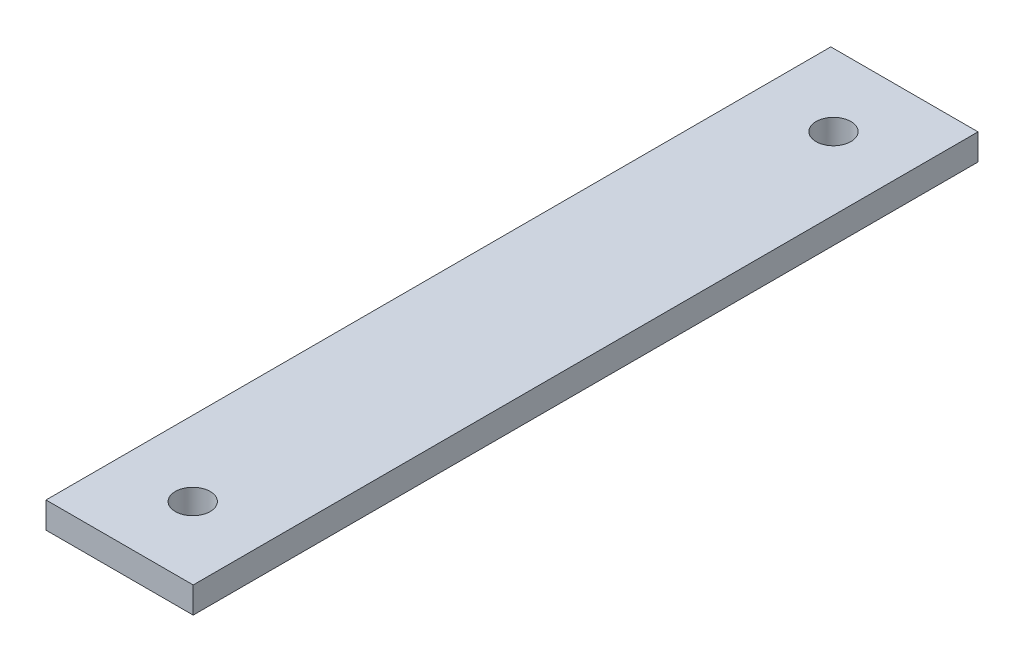
SolidWorks part; units mm, degrees
ref_plane "Piano frontale" through (0, 0, 0) normal (0, 0, 1) x (1, 0, 0)
ref_plane "Piano superiore" through (0, 0, 0) normal (0, 1, 0) x (1, 0, 0)
ref_plane "Piano destro" through (0, 0, 0) normal (1, 0, 0) x (0, 0, -1)
sketch "Schizzo1" plane through (0, 0, 0) normal (0, 1, 0) x (1, 0, 0)
  line L0 (0, 26.1688) -> (0, -29.0254) construction
  line L1 (-37.2892, 0) -> (39.0236, 0) construction
  line L3 (-4.22, -22.5) -> (4.22, -22.5)
  line L4 (-4.22, -22.5) -> (-4.22, 22.5)
  line L5 (-4.22, 22.5) -> (4.22, 22.5)
  line L6 (4.22, -22.5) -> (4.22, 22.5)
  line L7 (-4.22, -22.5) -> (4.22, 22.5) construction
  line L8 (-4.22, 22.5) -> (4.22, -22.5) construction
  point P5 (0, 0)
  dimension "D1" = 45
  dimension "D2" = 8.44
extrude "Estrusione-Estrusione1" add sketch "Schizzo1" along normal blind 1.5
sketch "Schizzo2" plane through (0, 1.5, 0) normal (0, 1, 0) x (1, 0, 0)
  line L0 (0, 23.9805) -> (0, -25.0782) construction
  line L1 (-17.6476, 0) -> (17.7743, 0) construction
  line L2 (-17.6476, 18.37) -> (17.7743, 18.37) construction
  line L3 (4.22, 22.5) -> (-4.22, 22.5) construction
  circle A0 centre (0.0633, 18.37) radius 1
  circle A1 centre (0.0633, -18.37) radius 1
  dimension "D1" = 4.13
extrude "Taglio-Estrusione1" cut sketch "Schizzo2" against normal up to surface (1.5 mm away) up to face at (0, 0, 0)
